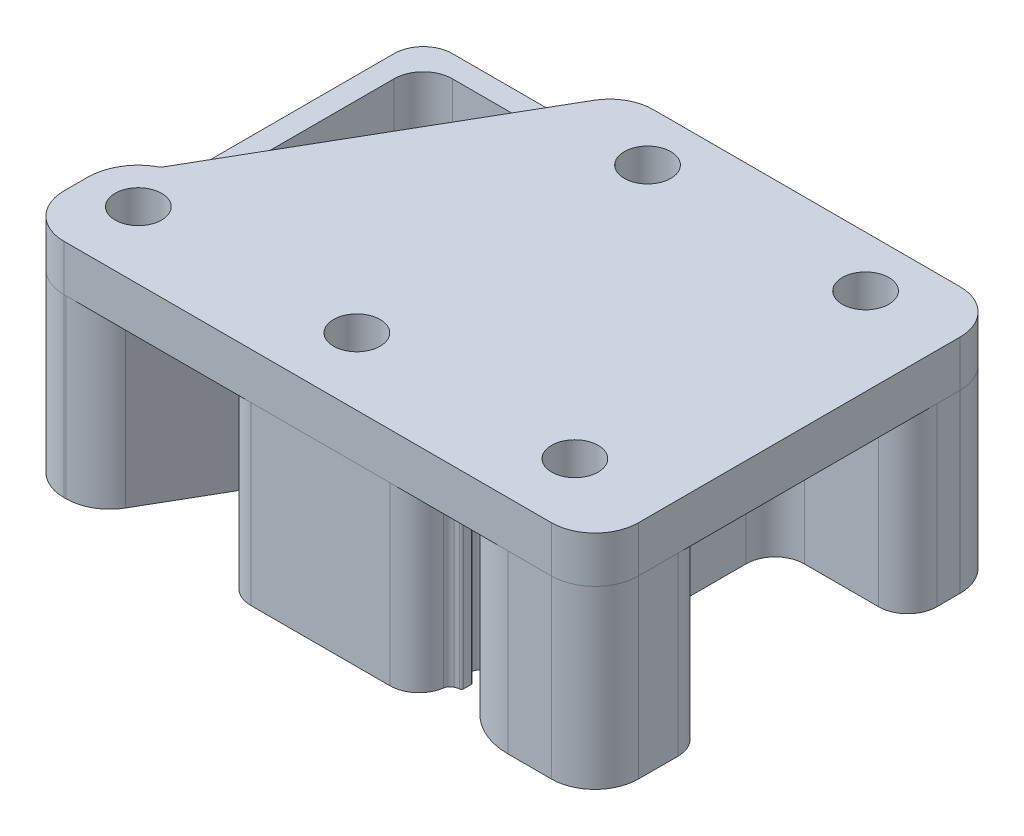
SolidWorks part; units mm, degrees
material "AISI 1045 Steel, cold drawn"
ref_plane "Front Plane" through (0, 0, 0) normal (0, 0, 1) x (1, 0, 0)
ref_plane "Top Plane" through (0, 0, 0) normal (0, 1, 0) x (1, 0, 0)
ref_plane "Right Plane" through (0, 0, 0) normal (1, 0, 0) x (0, 0, -1)
sketch "Sketch1" plane through (0, 0, 0) normal (0, 1, 0) x (1, 0, 0)
  line L0 (-13.5, -13.5) -> (-13.5, -14.619)
  line L1 (7.5, -10) -> (-7.5, -10) construction
  line L2 (7.5, -10) -> (7.5, 10) construction
  line L3 (7.5, 10) -> (-7.5, 10) construction
  line L4 (-7.5, -10) -> (-7.5, 10) construction
  line L5 (7.5, -10) -> (-7.5, 10) construction
  line L6 (7.5, 10) -> (-7.5, -10) construction
  line L7 (13.5, -13.5) -> (-13.5, -13.5) construction
  line L8 (13.5, -13.5) -> (13.5, 13.5)
  line L9 (13.5, 13.5) -> (-13.5, 13.5)
  line L10 (-13.5, -13.5) -> (-13.5, 13.5)
  line L11 (13.5, -13.5) -> (-13.5, 13.5) construction
  line L12 (13.5, 13.5) -> (-13.5, -13.5) construction
  line L13 (-13.5, -14.619) -> (13.5, -14.619)
  line L14 (13.5, -14.619) -> (13.5, -13.5)
  point P0 (0, 0)
  point P6 (0, 0)
  dimension "D1" = 15
  dimension "D2" = 27
  dimension "D3" = 1.119
  dimension "D4" = 20
extrude "Boss-Extrude1" add sketch "Sketch1" along normal mid plane 12.1
hole_wizard "M3 Clearance Hole1" positions "Sketch2" profile "Sketch3" hole size "M3" standard "ANSI Metric" end condition through all
sketch "Sketch2" plane through (0, 6.05, 0) normal (0, 1, 0) x (1, 0, 0)
  point P0 (-7.5, 10)
  point P3 (7.5, 10)
  point P6 (7.5, -10)
  point P9 (-7.5, -10)
sketch "Sketch3" plane through (-7.5, 6.05, -10) normal (1, 0, 0) x (0, 0, 1)
  line L0 (0, 0) -> (0, 12.1)
  line L1 (0, 12.1) -> (1.6, 12.1)
  line L2 (1.6, 12.1) -> (1.6, 0)
  line L5 (1.6, 0) -> (0, 0)
  line L11 (0, -6.35) -> (0, 107.95) construction
  dimension "Thru Hole Dia." = 3.2
  dimension "Thru Hole Depth" = 12.1
sketch "Sketch6" plane through (0, 6.05, 0) normal (0, 1, 0) x (1, 0, 0)
  line L0 (13.5, 13.5) -> (-13.5, 13.5) construction
  line L1 (-13.5, -14.619) -> (-28, -14.619)
  line L2 (-13.5, -14.619) -> (-13.5, 13.5)
  line L3 (-13.5, 13.5) -> (-28, 13.5)
  line L4 (-28, -14.619) -> (-28, 13.5)
  dimension "D1" = 28
extrude "Boss-Extrude3" add sketch "Sketch6" against normal up to surface (12.1 mm away) up to face at (-7.5, -6.05, -8.4)
sketch "Sketch8" plane through (0, 6.05, 0) normal (0, 1, 0) x (1, 0, 0)
  line L0 (-28, -14.619) -> (13.5, -14.619) construction
  line L2 (2.881, -10) -> (2.881, 4)
  line L3 (2.881, 4) -> (1.361, 4)
  line L4 (1.361, -14.619) -> (1.361, 4)
  line L5 (7.5, -14.619) -> (1.361, -14.619)
  arc A0 (2.881, -10) -> (7.5, -14.619) centre (7.5, -10) ccw
  dimension "D1" = 1.52
  dimension "D2" = 14
extrude "Cut-Extrude2" cut sketch "Sketch8" against normal up to surface (12.1 mm away)
sketch "Sketch9" plane through (0, 6.05, 0) normal (0, 1, 0) x (1, 0, 0)
  line L1 (2.881, 4) -> (6.306, 4)
  line L2 (2.881, 4) -> (2.881, -8)
  line L3 (2.881, -8) -> (6.306, -8)
  line L4 (6.306, 4) -> (6.306, -8)
  dimension "D1" = 3.425
  dimension "D2" = 12
extrude "Cut-Extrude3" cut sketch "Sketch9" against normal up to surface (12.1 mm away)
sketch "Sketch11" plane through (0, 6.05, 0) normal (0, 1, 0) x (1, 0, 0)
  line L1 (2.111, 0.7046) -> (2.111, 4.8734) construction
  line L4 (2.365, -998.8465) -> (2.365, 49001.1535) construction
  line L5 (2.111, 2.2598) -> (2.111, 2)
  line L6 (1.361, 3) -> (2.111, 3) construction
  line L7 (1.361, 4) -> (1.361, -14.619) construction
  line L8 (6.306, 4) -> (1.361, 4) construction
  line L9 (2.111, 2) -> (1.361, 2)
  line L10 (1.361, 2) -> (1.361, 4)
  line L11 (2.111, 4) -> (1.361, 4)
  line L12 (2.111, 3.7402) -> (2.111, 4)
  arc A2 (1.6728, 3.4989) -> (1.6728, 2.5011) centre (1.916, 3) ccw
  arc A4 (1.6728, 2.5011) -> (1.9806, 2.4085) centre (2.111, 3.4) ccw
  arc A5 (2.111, 2.2598) -> (1.9806, 2.4085) centre (1.961, 2.2598) ccw
  arc A6 (2.111, 3.7402) -> (1.9806, 3.5915) centre (1.961, 3.7402) cw
  arc A7 (1.6728, 3.4989) -> (1.9806, 3.5915) centre (2.111, 2.6) cw
  point P7 (1.361, 3)
  line M19 (1.361, -14.619) -> (1.361, 4)
  line M20 (1.361, 4) -> (6.306, 4)
  dimension "D3" = 0.555
  dimension "D4" = 1
  dimension "D5" = 1
  dimension "D6" = 0.15
  dimension "D1" = 0.254
  dimension "D2" = 0.75
  dimension "D7" = 1
extrude "Boss-Extrude4" add sketch "Sketch11" against normal up to surface (12.1 mm away) contours A2 A7 A6 L12 L10 M20 | L5 A5 A4 A2 L9 M19
pattern_linear "LPattern1" count 9 spacing 2 along (0, 0, 1) of "Boss-Extrude4"
sketch "Sketch12" plane through (0, 6.05, 0) normal (0, 1, 0) x (1, 0, 0)
  circle A0 centre (2.111, 4) radius 0.5
  circle A1 centre (6.306, 4) radius 0.5
  circle A2 centre (6.306, -8) radius 0.5
  dimension "D1" = 1
extrude "Cut-Extrude5" cut sketch "Sketch12" against normal up to surface (12.1 mm away)
sketch "Sketch13" plane through (0, 6.05, 0) normal (0, 1, 0) x (1, 0, 0)
  line L3 (2.111, -14) -> (1.361, -14) construction
  line L4 (2.111, -13.7402) -> (2.111, -14) construction
  line L5 (2.111, -14) -> (1.361, -14)
  line L6 (2.111, -13.7402) -> (2.111, -14)
  line L7 (1.361, -14) -> (1.361, -13)
  arc A6 (1.6728, -12.5011) -> (1.6728, -13.4989) centre (1.916, -13) ccw construction
  arc A7 (1.6728, -13.4989) -> (1.9806, -13.5915) centre (2.111, -12.6) ccw construction
  arc A8 (2.111, -13.7402) -> (1.9806, -13.5915) centre (1.961, -13.7402) ccw construction
  arc A9 (1.361, -13) -> (1.6728, -13.4989) centre (1.916, -13) ccw
  arc A10 (1.6728, -13.4989) -> (1.9806, -13.5915) centre (2.111, -12.6) ccw
  arc A11 (2.111, -13.7402) -> (1.9806, -13.5915) centre (1.961, -13.7402) ccw
extrude "Cut-Extrude6" cut sketch "Sketch13" against normal up to surface (12.1 mm away)
fillet "Fillet3" radius 0.5 7 edges at (5.806, 0, 8) (6.306, 0, 7.5) (5.806, 0, -4) (6.306, 0, -3.5) (2.611, 0, -4) (1.8595, 0, -3.5679) (2.881, 0, 8)
sketch "Sketch17" plane through (0, 6.05, 0) normal (0, 1, 0) x (1, 0, 0)
  line L0 (-21.1595, -14.619) -> (-15.513, -17.879)
  line L11 (-6.4019, 5.9019) -> (-3.8038, 4.4019) construction
  line L12 (-6.4019, 5.9019) -> (-2.9019, 11.9641) construction
  line L13 (-3.8038, 4.4019) -> (-0.3038, 10.4641) construction
  line L14 (-2.9019, 11.9641) -> (-0.3038, 10.4641) construction
  line L15 (-4.201, 12.7141) -> (0.9952, 9.7141) construction
  line L16 (-4.201, 12.7141) -> (-2.701, 15.3122) construction
  line L17 (0.9952, 9.7141) -> (2.4952, 12.3122) construction
  line L18 (-2.701, 15.3122) -> (2.4952, 12.3122) construction
  line L19 (-5.1029, 5.1519) -> (-0.1029, 13.8122) construction
  line L20 (-21.1595, -14.619) -> (-8.5843, 7.1619)
  line L21 (-15.513, -17.879) -> (-2.9378, 3.9019)
  line L22 (-8.5843, 7.1619) -> (-2.9378, 3.9019)
  line L23 (-22.5782, -10.8263) -> (-19.8719, -12.3888) construction
  line L24 (-22.5782, -10.8263) -> (-12.5782, 6.4942) construction
  line L25 (-19.8719, -12.3888) -> (-9.8719, 4.9317) construction
  line L26 (-12.5782, 6.4942) -> (-9.8719, 4.9317) construction
  line L27 (-28, -14.619) -> (1.361, -14.619) construction
  line L28 (-14.8719, -3.7285) -> (-17.5782, -2.166) construction
  circle A0 centre (-7.5, 10) radius 1.6 construction
  circle A1 centre (-7.5, -10) radius 1.6 construction
  dimension "D1" = 6.52
  dimension "D3" = 3
  dimension "D10" = 3
  dimension "D2" = 6
  dimension "D4" = 3
  dimension "D5" = 10
  dimension "D6" = 3.125
  dimension "D7" = 2.5
  dimension "D8" = 60
  dimension "D9" = 3
  dimension "D11" = 20
extrude "Cut-Extrude7" cut sketch "Sketch17" against normal up to surface (12.1 mm away)
sketch "Sketch18" plane through (0, 6.05, 0) normal (0, 1, 0) x (1, 0, 0)
  line L0 (-26.0342, -14.619) -> (-26.0342, -10)
  line L2 (-14.1485, 10.3744) -> (-26.7237, -11.4065)
  line L3 (-12.344, 13.5) -> (-24.1063, -6.8729)
  line L4 (-12.344, 13.5) -> (-28, 13.5)
  line L5 (-28, 13.5) -> (-28, -14.619)
  line L7 (-28, -14.619) -> (-21.1595, -14.619) construction
  line L8 (-8.5843, 7.1619) -> (-21.1595, -14.619) construction
  line L10 (-28, -14.619) -> (-26.0342, -14.619)
  arc A2 (-24.1063, -6.8729) -> (-26.0342, -10) centre (-22.5342, -10) ccw
  point P0 (-7.5, -10)
  dimension "D2" = 3.5
  dimension "D1" = 6.425
extrude "Cut-Extrude8" cut sketch "Sketch18" against normal up to surface (12.1 mm away)
hole_wizard "M3 Clearance Hole2" positions "Sketch19" profile "Sketch20" hole size "M3" standard "ANSI Metric" end condition up to next
sketch "Sketch19" plane through (0, 6.05, 0) normal (0, 1, 0) x (1, 0, 0)
  point P0 (-22.5342, -10)
sketch "Sketch20" plane through (-22.5342, 6.05, 10) normal (1, 0, 0) x (0, 0, 1)
  line L0 (0, 0) -> (0, 12.1)
  line L1 (0, 12.1) -> (1.6, 12.1)
  line L2 (1.6, 12.1) -> (1.6, 0)
  line L5 (1.6, 0) -> (0, 0)
  line L11 (0, -6.35) -> (0, 107.95) construction
  dimension "Thru Hole Dia." = 3.2
  dimension "Thru Hole Depth" = 12.1
fillet "Fillet4" radius 3 5 edges at (13.5, 0, 14.619) (13.5, 0, -13.5) (-12.344, 0, -13.5) (-26.0342, 0, 14.619) (-21.1595, 0, 14.619)
sketch "Sketch21" plane through (0, 6.05, 0) normal (0, 1, 0) x (1, 0, 0)
  line L0 (-8.5843, 7.1619) -> (-20.2935, -13.119) construction
  line L1 (-17.8343, -8.8595) -> (-20.8004, -7.147)
  line L2 (-17.8343, -8.8595) -> (-9.3343, 5.8629)
  line L3 (-20.8004, -7.147) -> (-12.3004, 7.5754)
  line L4 (-9.3343, 5.8629) -> (-12.3004, 7.5754)
  line L5 (-2.9378, 3.9019) -> (-8.5843, 7.1619) construction
  dimension "D3" = 17
  dimension "D1" = 3.425
  dimension "D2" = 1.5
extrude "Cut-Extrude9" cut sketch "Sketch21" against normal up to surface (12.1 mm away)
sketch "Sketch22" plane through (0, 6.05, 0) normal (0, 1, 0) x (1, 0, 0)
  circle A0 centre (-20.8004, -7.147) radius 0.5
  circle A1 centre (-12.3004, 7.5754) radius 0.5
  circle A2 centre (-8.5843, 7.1619) radius 0.5
  circle A3 centre (-2.9378, 3.9019) radius 0.5
  arc A4 (2.544, 4.25) -> (1.6303, 3.8625) centre (2.111, 4) ccw construction
extrude "Cut-Extrude10" cut sketch "Sketch22" against normal up to surface (12.1 mm away)
fillet "Fillet5" radius 0.5 10 edges at (-17.8343, 0, 8.8595) (-3.1878, 0, -3.4689) (-3.3708, 0, -4.1519) (-8.8343, 0, -6.7289) (-8.1513, 0, -6.9119) (-11.8674, 0, -7.3254) (-12.5504, 0, -7.1424) (-20.5504, 0, 6.714) (-20.3674, 0, 7.397) (-9.3343, 0, -5.8629)
ref_plane "Plane2" through (6.9551, 0, -12.0466) normal (0.5, 0, -0.866) x (-0.866, 0, -0.5)
sketch "Sketch29" plane through (0, 6.05, 0) normal (0, 1, 0) x (1, 0, 0)
  line L0 (-13.21, 12) -> (-24.1063, -6.8729) construction
  line L1 (-26.0342, -11.619) -> (-26.0342, -10) construction
  line L2 (13.5, -11.619) -> (13.5, 10.5) construction
  line L3 (10.5, 13.5) -> (-10.6119, 13.5) construction
  line L5 (-23.0342, -14.619) -> (10.5, -14.619)
  line L6 (-26.0342, -11.619) -> (-26.0342, -10)
  line L7 (13.5, -11.619) -> (13.5, 10.5)
  line L8 (10.5, 13.5) -> (-10.6119, 13.5)
  line L10 (-13.21, 12) -> (-24.1063, -6.8729)
  arc A0 (-24.1063, -6.8729) -> (-26.0342, -10) centre (-22.5342, -10) ccw construction
  arc A1 (-26.0342, -11.619) -> (-23.0342, -14.619) centre (-23.0342, -11.619) ccw construction
  arc A2 (10.5, -14.619) -> (13.5, -11.619) centre (10.5, -11.619) ccw construction
  arc A3 (13.5, 10.5) -> (10.5, 13.5) centre (10.5, 10.5) ccw construction
  arc A4 (-10.6119, 13.5) -> (-13.21, 12) centre (-10.6119, 10.5) ccw construction
  arc A5 (-24.1063, -6.8729) -> (-26.0342, -10) centre (-22.5342, -10) ccw
  arc A6 (-26.0342, -11.619) -> (-23.0342, -14.619) centre (-23.0342, -11.619) ccw
  arc A7 (10.5, -14.619) -> (13.5, -11.619) centre (10.5, -11.619) ccw
  arc A8 (13.5, 10.5) -> (10.5, 13.5) centre (10.5, 10.5) ccw
  arc A9 (-10.6119, 13.5) -> (-13.21, 12) centre (-10.6119, 10.5) ccw
  circle A12 centre (-22.5342, -10) radius 1.6 construction
  circle A13 centre (-7.5, -10) radius 1.6 construction
  circle A14 centre (7.5, -10) radius 1.6 construction
  circle A15 centre (7.5, 10) radius 1.6 construction
  circle A16 centre (-7.5, 10) radius 1.6 construction
  circle A17 centre (-22.5342, -10) radius 1.6
  circle A18 centre (-7.5, -10) radius 1.6
  circle A19 centre (7.5, -10) radius 1.6
  circle A20 centre (7.5, 10) radius 1.6
  circle A21 centre (-7.5, 10) radius 1.6
extrude "Boss-Extrude7" add sketch "Sketch29" along normal blind 3.175 separate body
hole_wizard "CBORE for M3 SHCS1" positions "Sketch23" profile "Sketch25" counterbore size "M3" standard "ANSI Metric" end condition up to next
sketch "Sketch23" plane through (6.9551, 0, -12.0466) normal (0.5, 0, -0.866) x (-0.866, 0, -0.5)
  line L0 (4.4952, -6.05) -> (9.4952, 6.05) construction
  line L1 (-2.3433, -6.05) -> (15.9402, -6.05) construction
  line L3 (-2.3433, 6.05) -> (15.9402, 6.05) construction
  point P15 (6.9952, 0)
  dimension "D1" = 5
sketch "Sketch25" plane through (0.8971, 0, -15.5442) normal (0, 1, 0) x (-0.866, 0, -0.5)
  line L0 (0, 0) -> (0, 12)
  line L1 (0, 12) -> (1.6, 12)
  line L3 (1.6, 12) -> (1.6, 6)
  line L4 (1.6, 6) -> (3.25, 6)
  line L5 (3.25, 6) -> (3.25, 0)
  line L7 (3.25, 0) -> (0, 0)
  line L11 (0, -6.35) -> (0, 107.95) construction
  dimension "Thru Hole Dia." = 3.2
  dimension "Thru Hole Depth" = 12
  dimension "C'Bore Dia." = 6.5
  dimension "C'Bore Depth" = 6
sketch "Sketch30" plane through (0, 6.05, 0) normal (0, 1, 0) x (1, 0, 0)
  line L1 (3.381, -8) -> (5.44, -8) construction
  line L2 (6.306, -7.134) -> (6.306, 3.134) construction
  line L3 (5.44, 4) -> (2.977, 4) construction
  line L4 (3.381, -8) -> (5.44, -8)
  line L5 (6.306, -7.134) -> (6.306, 3.134)
  line L6 (5.44, 4) -> (2.977, 4)
  line L7 (-18.0843, -9.2926) -> (-9.0843, 6.2959)
  line L8 (-20.0504, -7.5801) -> (-18.2673, -8.6095) construction
  line L9 (-12.7335, 6.8254) -> (-20.3674, -6.397) construction
  line L10 (-9.7673, 6.1129) -> (-11.5504, 7.1424) construction
  line L11 (-20.0504, -7.5801) -> (-18.2673, -8.6095)
  line L12 (-12.7335, 6.8254) -> (-20.3674, -6.397)
  line L13 (-9.7673, 6.1129) -> (-11.5504, 7.1424)
  line L14 (2.881, -8.5) -> (2.881, 4.0093)
  arc A0 (3.381, -8) -> (2.881, -8.5) centre (3.381, -8.5) ccw construction
  arc A1 (5.873, -8.25) -> (5.44, -8) centre (5.44, -8.5) ccw construction
  arc A2 (5.873, -8.25) -> (6.556, -7.567) centre (6.306, -8) ccw construction
  arc A3 (6.306, -7.134) -> (6.556, -7.567) centre (6.806, -7.134) ccw construction
  arc A4 (6.556, 3.567) -> (6.306, 3.134) centre (6.806, 3.134) ccw construction
  arc A5 (6.556, 3.567) -> (5.873, 4.25) centre (6.306, 4) ccw construction
  arc A6 (5.44, 4) -> (5.873, 4.25) centre (5.44, 4.5) ccw construction
  arc A7 (2.544, 4.25) -> (2.977, 4) centre (2.977, 4.5) ccw construction
  arc A8 (3.381, -8) -> (2.881, -8.5) centre (3.381, -8.5) ccw
  arc A9 (5.873, -8.25) -> (5.44, -8) centre (5.44, -8.5) ccw
  arc A10 (5.873, -8.25) -> (6.556, -7.567) centre (6.306, -8) ccw
  arc A11 (6.306, -7.134) -> (6.556, -7.567) centre (6.806, -7.134) ccw
  arc A12 (6.556, 3.567) -> (6.306, 3.134) centre (6.806, 3.134) ccw
  arc A13 (6.556, 3.567) -> (5.873, 4.25) centre (6.306, 4) ccw
  arc A14 (5.44, 4) -> (5.873, 4.25) centre (5.44, 4.5) ccw
  arc A15 (2.881, 4.0093) -> (2.977, 4) centre (2.977, 4.5) ccw
  arc A17 (-18.0843, -9.2926) -> (-18.2673, -8.6095) centre (-18.5173, -9.0426) ccw construction
  arc A18 (-20.0504, -7.5801) -> (-20.5504, -7.5801) centre (-20.3004, -8.0131) ccw construction
  arc A19 (-20.8004, -6.647) -> (-20.3674, -6.397) centre (-20.8004, -6.147) ccw construction
  arc A20 (-12.7335, 6.8254) -> (-12.7335, 7.3254) centre (-13.1665, 7.0754) ccw construction
  arc A21 (-11.8004, 7.5754) -> (-12.7335, 7.3254) centre (-12.3004, 7.5754) ccw construction
  arc A22 (-11.8004, 7.5754) -> (-11.5504, 7.1424) centre (-11.3004, 7.5754) ccw construction
  arc A23 (-9.7673, 6.1129) -> (-9.0843, 6.2959) centre (-9.5173, 6.5459) ccw construction
  arc A24 (-18.0843, -9.2926) -> (-18.2673, -8.6095) centre (-18.5173, -9.0426) ccw
  arc A25 (-20.0504, -7.5801) -> (-20.5504, -7.5801) centre (-20.3004, -8.0131) ccw
  arc A26 (-20.8004, -6.647) -> (-20.3674, -6.397) centre (-20.8004, -6.147) ccw
  arc A27 (-12.7335, 6.8254) -> (-12.7335, 7.3254) centre (-13.1665, 7.0754) ccw
  arc A28 (-11.8004, 7.5754) -> (-12.7335, 7.3254) centre (-12.3004, 7.5754) ccw
  arc A29 (-11.8004, 7.5754) -> (-11.5504, 7.1424) centre (-11.3004, 7.5754) ccw
  arc A30 (-9.7673, 6.1129) -> (-9.0843, 6.2959) centre (-9.5173, 6.5459) ccw
  arc A31 (-20.8004, -6.647) -> (-20.5504, -7.5801) centre (-20.8004, -7.147) ccw construction
  arc A32 (-20.8004, -6.647) -> (-20.5504, -7.5801) centre (-20.8004, -7.147) ccw
extrude "Boss-Extrude8" add sketch "Sketch30" against normal up to surface (12.1 mm away)
fillet "Fillet6" radius 1 1 edges at (2.881, 0, -4.0093)
sketch "Sketch31" plane through (0, 6.05, 0) normal (0, 1, 0) x (1, 0, 0)
  line L0 (13.5, 6.9) -> (4.381, 6.9)
  line L2 (4.381, 6.9) -> (4.381, -6.9)
  line L3 (4.381, -6.9) -> (13.5, -6.9)
  line L4 (2.881, -10) -> (2.881, 3.4759) construction
  line L6 (13.5, 6.9) -> (13.5, -6.9)
  line L7 (13.5, -11.619) -> (13.5, 10.5) construction
  circle A0 centre (7.5, -10) radius 1.6 construction
  circle A1 centre (7.5, 10) radius 1.6 construction
  dimension "D1" = 3.1
  dimension "D2" = 3.1
  dimension "D3" = 1.5
extrude "Cut-Extrude11" cut sketch "Sketch31" against normal up to surface (12.1 mm away)
sketch "Sketch32" plane through (0, 6.05, 0) normal (0, 1, 0) x (1, 0, 0)
  line L0 (-10.0574, 7.6105) -> (-19.366, -8.5125)
  line L1 (-9.0173, 6.4119) -> (-20.2935, -13.119) construction
  line L2 (-13.21, 12) -> (-24.1063, -6.8729) construction
  line L3 (-13.21, 12) -> (-24.1063, -6.8729)
  line L5 (10.5, 13.5) -> (-10.6119, 13.5) construction
  line L6 (-7.5, 13.5) -> (-10.6119, 13.5)
  arc A0 (-19.366, -8.5125) -> (-24.1063, -6.8729) centre (-22.5342, -10) ccw
  arc A1 (-24.1063, -6.8729) -> (-26.0342, -10) centre (-22.5342, -10) ccw construction
  arc A2 (-7.5, 13.5) -> (-10.0574, 7.6105) centre (-7.5, 10) ccw
  arc A3 (-10.6119, 13.5) -> (-13.21, 12) centre (-10.6119, 10.5) ccw construction
  arc A4 (-10.6119, 13.5) -> (-13.21, 12) centre (-10.6119, 10.5) ccw
  dimension "D1" = 1.5
extrude "Cut-Extrude12" cut sketch "Sketch32" against normal up to surface (12.1 mm away)
sketch "Sketch34" plane through (0, -6.05, 0) normal (0, -1, 0) x (1, 0, 0)
  line L0 (0.111, -6.1826) -> (-7.4426, 6.9005)
  line L1 (-3.3708, -3.1519) -> (-13.6309, 14.619) construction
  line L2 (0.111, -6.1826) -> (0.111, 12.619)
  line L4 (0.111, 12.619) -> (-5.8414, 12.619)
  line L5 (2.111, 10.2598) -> (2.111, 9.7402) construction
  line L7 (-13.6309, 14.619) -> (1.361, 14.619) construction
  circle A2 centre (-7.5, 10) radius 3.1
  arc A3 (-7.4426, 6.9005) -> (-5.8414, 12.619) centre (-7.5, 10) ccw
  dimension "D2" = 1.5
  dimension "D3" = 2
  dimension "D4" = 2
  dimension "D1" = 1.5
extrude "Cut-Extrude14" cut sketch "Sketch34" against normal up to surface (12.1 mm away)
sketch "Sketch35" plane through (0, -6.05, 0) normal (0, -1, 0) x (1, 0, 0)
  line L0 (-4.9175, -11.9731) -> (0.7117, -8.7231) construction
  line L1 (-7.5622, -13.5) -> (1.2713, -8.4)
  line L2 (10.5, -13.5) -> (-7.5, -13.5) construction
  line L3 (1.2713, -8.4) -> (4.3871, -8.4)
  line L4 (7.5, -13.5) -> (-7.5622, -13.5)
  line L6 (4.381, -6.9) -> (13.5, -6.9) construction
  circle A1 centre (7.5, -10) radius 1.6 construction
  arc A3 (4.3871, -8.4) -> (7.5, -13.5) centre (7.5, -10) ccw
  dimension "D1" = 1.5
extrude "Cut-Extrude15" cut sketch "Sketch35" against normal up to surface (12.1 mm away)
fillet "Fillet7" radius 2 9 edges at (-13.6309, 0, 14.619) (1.361, 0, 14.619) (13.5, 0, 6.9) (4.381, 0, 6.9) (13.5, 0, -6.9) (4.381, 0, -6.9) (-19.366, 0, 8.5125) (-7.5612, 0, -13.4995) (-10.0574, 0, -7.6105)
fillet "Fillet8" radius 1 6 edges at (0.111, 0, 12.619) (0.111, 0, -6.1826) (-5.8414, 0, 12.619) (-7.4426, 0, 6.9005) (4.3871, 0, -8.4) (1.2713, 0, -8.4)
sketch "Sketch36" plane through (0, 6.05, 0) normal (0, 1, 0) x (1, 0, 0)
  line L0 (2.881, 4.4759) -> (2.881, 3.4759)
  line L1 (1.611, 4) -> (1.611, 4.4759)
  arc A0 (1.611, 4.4759) -> (2.881, 4.4759) centre (2.246, 4.4759) cw
  arc A3 (2.544, 4.25) -> (1.6303, 3.8625) centre (2.111, 4) ccw construction
  arc A4 (2.544, 4.25) -> (2.6117, 4.1586) centre (2.977, 4.5) ccw construction
  arc A5 (2.881, 3.4759) -> (2.6117, 4.1586) centre (1.881, 3.4759) ccw construction
  arc A6 (2.544, 4.25) -> (1.611, 4) centre (2.111, 4) ccw
  arc A7 (2.544, 4.25) -> (2.6117, 4.1586) centre (2.977, 4.5) ccw
  arc A8 (2.881, 3.4759) -> (2.6117, 4.1586) centre (1.881, 3.4759) ccw
  dimension "D1" = 1
extrude "Cut-Extrude16" cut sketch "Sketch36" against normal up to surface (12.1 mm away)
sketch "Sketch37" plane through (0, 6.05, 0) normal (0, 1, 0) x (1, 0, 0)
  line L0 (-10.6817, 6.5291) -> (-9.847, 7.9748)
  line L1 (-18.0522, -6.2369) -> (-10.6817, 6.5291) construction
  line L2 (1.0392, 8.534) -> (-6.9682, 13.1571) construction
  line L3 (-6.6764, 12.9886) -> (-6.9682, 13.1571)
  arc A0 (-6.6764, 12.9886) -> (-9.847, 7.9748) centre (-7.5, 10) ccw
  circle A1 centre (-7.5, 10) radius 1.6 construction
  arc A2 (-6.9682, 13.1571) -> (-8.5926, 13.3251) centre (-7.9682, 11.425) ccw construction
  arc A3 (-8.5926, 13.3251) -> (-10.6269, 8.4276) centre (-7.5, 10) ccw construction
  arc A4 (-10.6817, 6.5291) -> (-10.6269, 8.4276) centre (-12.4137, 7.5291) ccw construction
  arc A5 (-6.9682, 13.1571) -> (-8.5926, 13.3251) centre (-7.9682, 11.425) ccw
  arc A6 (-8.5926, 13.3251) -> (-10.6269, 8.4276) centre (-7.5, 10) ccw
  arc A7 (-10.6817, 6.5291) -> (-10.6269, 8.4276) centre (-12.4137, 7.5291) ccw
  dimension "D1" = 1.5
extrude "Cut-Extrude17" cut sketch "Sketch37" against normal up to surface (12.1 mm away)
fillet "Fillet9" radius 2 2 edges at (-6.6764, 0, -12.9886) (-9.847, 0, -7.9748)
sketch "Sketch38" plane through (0, 6.05, 0) normal (0, 1, 0) x (1, 0, 0)
  line L0 (-26.0342, -10) -> (-26.0342, 13.1)
  line L1 (-26.0342, 13.1) -> (-7.5, 13.1)
  line L2 (-24.5342, -7.1277) -> (-24.5342, 11.6)
  line L3 (-24.5342, 11.6) -> (-10.1552, 11.6)
  line L4 (-24.5342, -10) -> (-24.5342, 11.6) construction
  line L5 (-24.5342, 11.6) -> (-7.5, 11.6) construction
  arc A0 (-7.2093, 13.0863) -> (-10.3388, 8.7545) centre (-7.5, 10) ccw construction
  arc A1 (-7.5, 13.1) -> (-10.1552, 11.6) centre (-7.5, 10) ccw
  arc A2 (-20.7842, -6.9689) -> (-26.0342, -10) centre (-22.5342, -10) ccw construction
  arc A3 (-24.5342, -7.1277) -> (-26.0342, -10) centre (-22.5342, -10) ccw
  dimension "D1" = 1.5
extrude "Boss-Extrude9" add sketch "Sketch38" against normal up to surface (12.1 mm away)
fillet "Fillet10" radius 2 4 edges at (-24.5342, 0, 7.1277) (-10.1552, 0, -11.6) (-26.0342, 0, -13.1) (-24.5342, 0, -11.6)
sketch "Sketch39" plane through (0.9551, 0, -1.6543) normal (-0.5, 0, 0.866) x (0.866, 0, 0.5)
  circle A0 centre (-6.9952, 0) radius 1.6 construction
  circle A1 centre (-6.9952, 0) radius 1.6
extrude "Boss-Extrude10" add sketch "Sketch39" against normal up to surface (6 mm away)
